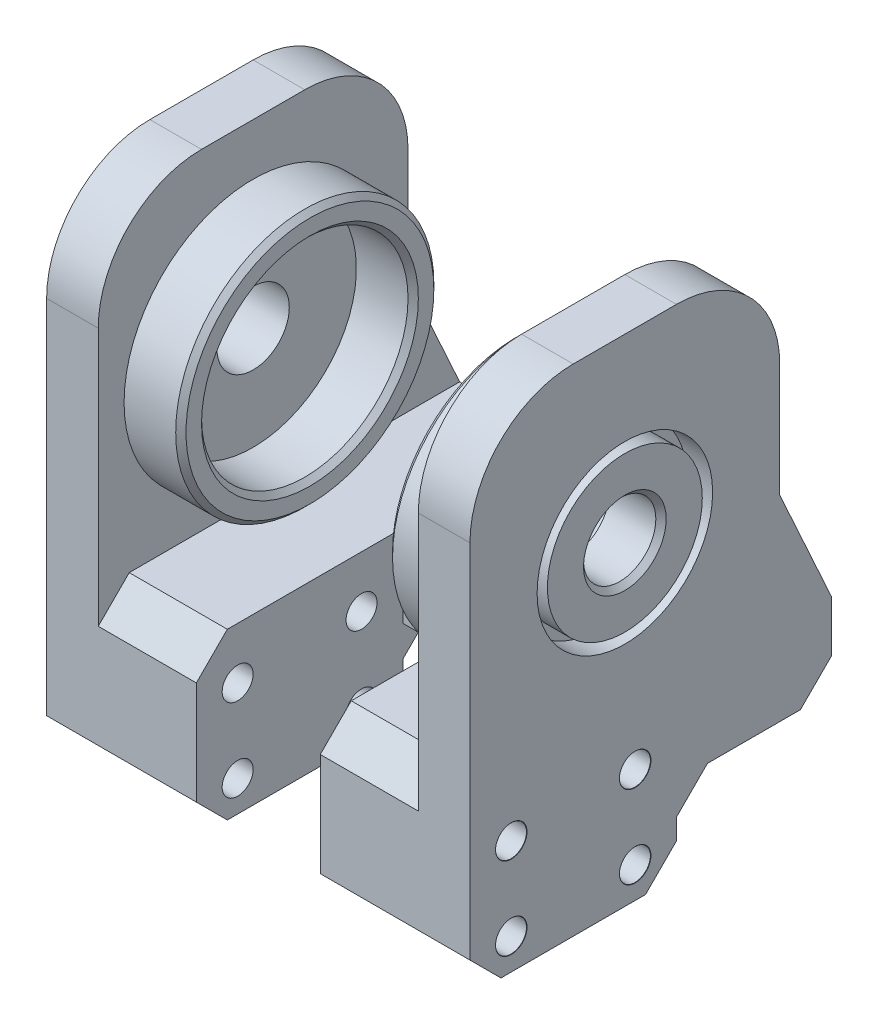
SolidWorks part; units mm, degrees
ref_plane "前视基准面" through (0, 0, 0) normal (0, 0, 1) x (1, 0, 0)
ref_plane "上视基准面" through (0, 0, 0) normal (0, 1, 0) x (1, 0, 0)
ref_plane "右视基准面" through (0, 0, 0) normal (1, 0, 0) x (0, 0, -1)
other "Configuration Table"
sketch "草图1" plane through (0, 0, 0) normal (0, 1, 0) x (1, 0, 0)
  circle A1 centre (0, 0) radius 13.5
  dimension "D2" = 27
extrude "凸台-拉伸1" add sketch "草图1" along normal blind 8
sketch "草图7" plane through (0, 0, 0) normal (0, -1, 0) x (1, 0, 0)
  line L1 (-17, 15) -> (17, 15)
  line L2 (-17, 15) -> (-17, -15)
  line L3 (-17, -15) -> (17, -15)
  line L4 (17, 15) -> (17, -15)
  line L5 (-17, 15) -> (17, -15) construction
  line L6 (-17, -15) -> (17, 15) construction
  circle A0 centre (0, 0) radius 13.5
  dimension "D1" = 27
  dimension "D2" = 34
  dimension "D3" = 30
extrude "凸台-拉伸2" add sketch "草图7" against normal blind 8
sketch "草图11" plane through (0, 0, 0) normal (0, -1, 0) x (1, 0, 0)
  line L0 (-17, -15) -> (17, -15) construction
  line L1 (-16, 15) -> (-21, 15)
  line L2 (-16, 15) -> (-16, -15)
  line L3 (-16, -15) -> (-21, -15)
  line L4 (-21, 15) -> (-21, -15)
  line L5 (15, 15) -> (20, 15)
  line L6 (15, 15) -> (15, -15)
  line L7 (15, -15) -> (20, -15)
  line L8 (20, 15) -> (20, -15)
  line L9 (17, 15) -> (-17, 15) construction
  line L10 (-17, 15) -> (-17, -15) construction
  line L11 (17, -15) -> (17, 15) construction
  dimension "D1" = 5
  dimension "D2" = 5
  dimension "D3" = 1
  dimension "D4" = 2
extrude "凸台-拉伸6" add sketch "草图11" against normal blind 40
fillet "圆角2" radius 10 4 edges at (17.5, 40, 15) (17.5, 40, -15) (-18.5, 40, -15) (-18.5, 40, 15)
sketch "草图12" plane through (20, 0, 0) normal (1, 0, 0) x (0, 0, -1)
  arc A0 (8.4173, 31.317) -> (8.4173, 33.683) centre (0, 32.5) ccw construction
  arc A1 (7.427, 31.4562) -> (7.427, 33.5438) centre (0, 32.5) ccw construction
  arc A2 (8.4173, 31.317) -> (8.4173, 33.683) centre (0, 32.5) ccw
  arc A3 (7.427, 31.4562) -> (7.427, 33.5438) centre (0, 32.5) ccw
sketch "草图13" plane through (20, 0, 0) normal (1, 0, 0) x (0, 0, -1)
  line L0 (5, 40) -> (-5, 40) construction
  line L1 (15, 30) -> (15, 0) construction
  circle A0 centre (0, 22.5) radius 7.5
  circle A1 centre (0, 22.5) radius 8.5
  dimension "D1" = 15
  dimension "D2" = 17
  dimension "D3" = 17.5
  dimension "D4" = 15
extrude "切除-拉伸3" cut sketch "草图13" against normal blind 2.5
sketch "草图14" plane through (20, 0, 0) normal (1, 0, 0) x (0, 0, -1)
  line L0 (5, 40) -> (-5, 40) construction
  line L1 (-15, 30) -> (-15, 0) construction
  circle A0 centre (0, 22.5) radius 3.5
  dimension "D1" = 7
  dimension "D2" = 17.5
  dimension "D3" = 15
extrude "切除-拉伸4" cut sketch "草图14" against normal up to surface (36 mm away)
sketch "草图15" plane through (-21, 0, 0) normal (1, 0, 0) x (0, 0, -1)
  line L0 (15, 30) -> (15, 0) construction
  line L1 (-5, 40) -> (5, 40) construction
  line L2 (0, 22.5) -> (30.7008, 22.5) construction
  line L3 (0, 22.5) -> (0, 55.041)
  circle A0 centre (0, 22.5) radius 11
  circle A4 centre (0, 11.5) radius 1.1
  circle A5 centre (-11, 22.5) radius 1.1
  circle A6 centre (11, 22.5) radius 1.1
  circle A7 centre (0, 33.5) radius 1.1
  dimension "D1" = 22
  dimension "D2" = 15
  dimension "D3" = 17.5
sketch "草图19" plane through (15, 0, 0) normal (-1, 0, 0) x (0, 0, 1)
  line L0 (-15, 30) -> (-15, 0) construction
  line L1 (5, 40) -> (-5, 40) construction
  line L2 (-6.0948, 16.4052) -> (17.6953, 40.1953)
  line L3 (-17.7953, 40.2953) -> (9.6159, 12.8841)
  line L4 (0, 22.5) -> (-30.7008, 22.5) construction
  circle A0 centre (0, 22.5) radius 11
  circle A9 centre (-7.7782, 14.7218) radius 1.25
  circle A10 centre (7.7782, 14.7218) radius 1.25
  circle A11 centre (-7.7782, 30.2782) radius 1.25
  circle A12 centre (7.7782, 30.2782) radius 1.8117
  dimension "D1" = 22
  dimension "D2" = 15
  dimension "D3" = 17.5
  dimension "D4" = 45
  dimension "D5" = 45
sketch "草图22" plane through (0, 0, 0) normal (0, -1, 0) x (1, 0, 0)
  line L0 (-21, -15) -> (20, -15) construction
  line L1 (20, -15) -> (-21, -15)
  line L2 (20, -15) -> (20, -20)
  line L3 (20, -20) -> (-21, -20)
  line L4 (-21, -15) -> (-21, -20)
  line L8 (-21, 0) -> (-21, -30.7008) construction
  line L9 (20, -15) -> (20, 15) construction
  dimension "D1" = 5
extrude "凸台-拉伸8" add sketch "草图22" against normal blind 8
sketch "草图23" plane through (0, 0, 15) normal (0, 0, 1) x (1, 0, 0)
  line L0 (20, 0) -> (-21, 0) construction
  line L1 (-6.5, 8) -> (5.5, 8)
  line L2 (-6.5, 8) -> (-6.5, 0)
  line L3 (-6.5, 0) -> (5.5, 0)
  line L4 (5.5, 8) -> (5.5, 0)
  line L6 (15, 8) -> (-16, 8) construction
  line L7 (-21, 30) -> (-21, 0) construction
  dimension "D1" = 12
  dimension "D2" = 14.5
extrude "切除-拉伸6" cut sketch "草图23" against normal blind 20
sketch "草图24" plane through (-21, 0, 0) normal (-1, 0, 0) x (0, 0, 1)
  line L0 (-20, 8) -> (-15, 19)
  line L1 (-15, 30) -> (-15, 8) construction
rib "筋1" sketch "草图24" sketch "草图24" thickness 5 extrusion direction parallel to sketch draft on no parameters "D1"=5
sketch "草图25" plane through (20, 0, 0) normal (1, 0, 0) x (0, 0, -1)
  line L0 (20, 8) -> (15, 19)
  line L1 (15, 30) -> (15, 8) construction
  line L2 (20, 8) -> (15, 8)
  line L3 (15, 8) -> (15, 19)
extrude "凸台-拉伸9" add sketch "草图25" against normal blind 4
hole_wizard "Ø3.0mm 暗销孔1" positions "3D草图5" profile "草图26" hole size "Ø3.0" standard "GB" end condition through all
sketch3d "3D草图5"
  line L0 (20, 0, -20) -> (20, 0, 15) construction
  point P0 (20, 3, 11)
  point P2 (20, 3, -1)
  dimension "D1" = 12
  dimension "D2" = 5
  dimension "D3" = 4
  dimension "D4" = 3
sketch "草图26" plane through (20, 3, 11) normal (0, 1, 0) x (0, 0, -1)
  line L0 (0, 0) -> (0, 41)
  line L1 (0, 41) -> (1.5, 41)
  line L2 (1.5, 41) -> (1.5, 0.025)
  line L3 (1.5, 0.025) -> (1.525, 0)
  line L5 (1.525, 0) -> (0, 0)
  line L6 (-1.5, 0.025) -> (-1.525, 0) construction
  line L11 (0, -6.35) -> (0, 107.95) construction
  dimension "通孔孔直径" = 3
  dimension "通孔孔深度" = 41
  dimension "近端锥形沉头孔直径" = 3.05
  dimension "近端锥形沉头孔角度" = 90
sketch "草图27" plane through (0, 0, 0) normal (0, -1, 0) x (1, 0, 0)
  line L1 (-21, 15) -> (-6.5, 15)
  line L2 (-21, 15) -> (-21, -5)
  line L3 (-21, -5) -> (-6.5, -5)
  line L4 (-6.5, 15) -> (-6.5, -5)
  line L5 (20, 15) -> (5.5, 15)
  line L6 (20, 15) -> (20, -5)
  line L7 (20, -5) -> (5.5, -5)
  line L8 (5.5, 15) -> (5.5, -5)
extrude "凸台-拉伸10" add sketch "草图27" along normal blind 8
hole_wizard "Ø3.0mm 暗销孔2" positions "3D草图6" profile "草图28" hole size "Ø3.0" standard "GB" end condition through all
sketch3d "3D草图6"
  line L0 (20, 30, 15) -> (20, -8, 15) construction
  line L1 (20, -8, -5) -> (20, 0, -5) construction
  circle A1 centre (19.975, 3, 11) radius 1.5 construction
  circle A2 centre (19.975, 3, -1) radius 1.5 construction
  point P0 (20, -5, 11)
  point P2 (20, -5, -1)
  point P11 (21.475, 3, 11)
  point P14 (21.475, 3, -1)
  dimension "D1" = 8
  dimension "D2" = 8
  dimension "D3" = 4
  dimension "D4" = 4
sketch "草图28" plane through (20, -5, 11) normal (0, 1, 0) x (0, 0, -1)
  line L0 (0, 0) -> (0, 41)
  line L1 (0, 41) -> (1.5, 41)
  line L2 (1.5, 41) -> (1.5, 0.025)
  line L3 (1.5, 0.025) -> (1.525, 0)
  line L5 (1.525, 0) -> (0, 0)
  line L6 (-1.5, 0.025) -> (-1.525, 0) construction
  line L11 (0, -6.35) -> (0, 107.95) construction
  dimension "通孔孔直径" = 3
  dimension "通孔孔深度" = 41
  dimension "近端锥形沉头孔直径" = 3.05
  dimension "近端锥形沉头孔角度" = 90
chamfer "倒角5" distance 3 angle 45 9 edges at (-0.5, 0, -20) (-11.25, 8, 15) (-13.75, 0, -5) (-13.75, -8, -5) (-13.75, -8, 15) (12.75, 0, -5) (12.75, -8, 15) (12.75, -8, -5) (10.25, 8, 15)
sketch "草图29" plane through (15, 0, 0) normal (-1, 0, 0) x (0, 0, 1)
  circle A0 centre (0, 22.5) radius 10
  circle A1 centre (0, 22.5) radius 12.5
  dimension "D1" = 20
  dimension "D2" = 25
extrude "凸台-拉伸11" add sketch "草图29" along normal blind 5.5
ref_plane "基准面1" through (-0.5, 0, 0) normal (-1, 0, 0) x (0, 0, 1)
mirror "镜向1" about plane through (-0.5, 0, 0) normal (-1, 0, 0) of "凸台-拉伸11", "切除-拉伸3", "切除-拉伸4"
chamfer "倒角4" distance 0.5 angle 45 6 edges at (20, 22.5, -3.5) (9.5, 22.5, 12.5) (-10.5, 22.5, 12.5) (-21, 22.5, -3.5) (-10.5, 22.5, 10) (9.5, 22.5, 10)
